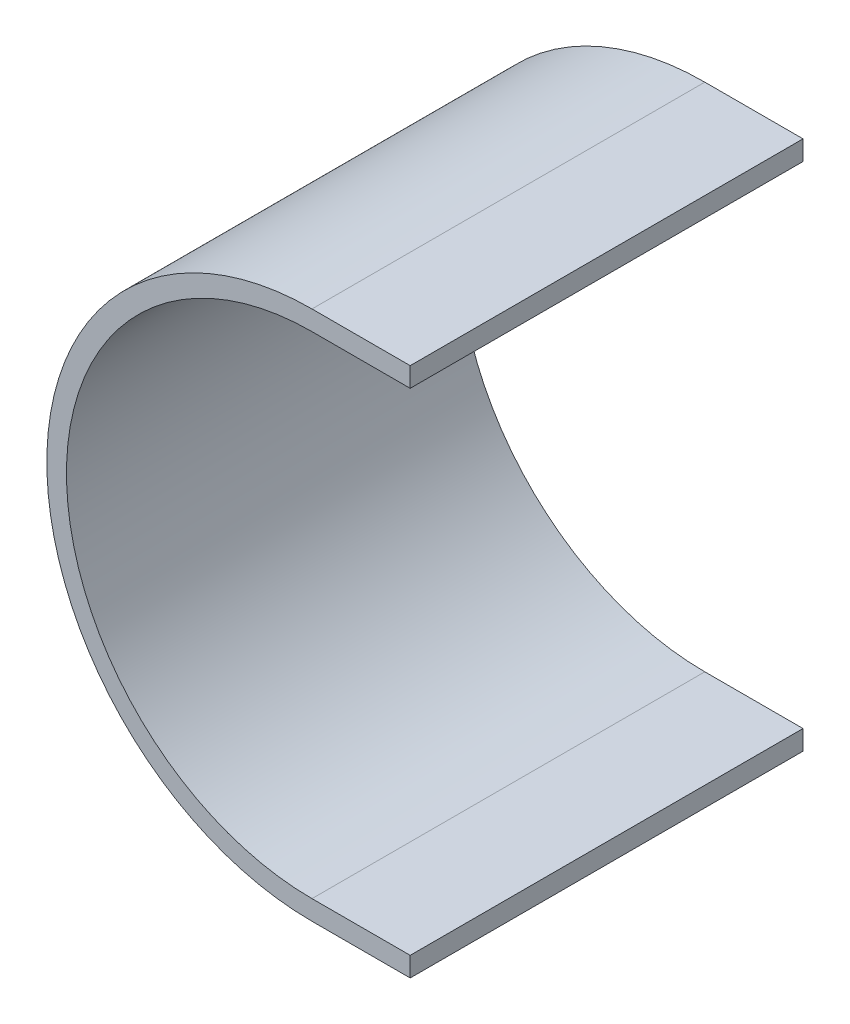
SolidWorks part; units mm, degrees
ref_plane "Front Plane" through (0, 0, 0) normal (0, 0, 1) x (1, 0, 0)
ref_plane "Top Plane" through (0, 0, 0) normal (0, 1, 0) x (1, 0, 0)
ref_plane "Right Plane" through (0, 0, 0) normal (1, 0, 0) x (0, 0, -1)
sketch "Sketch1" plane through (0, 0, 0) normal (0, 0, 1) x (1, 0, 0)
  line L3 (0, 81) -> (30, 81)
  line L5 (0, 75) -> (30, 75)
  line L6 (30, 81) -> (30, 75)
  line L7 (0, -81) -> (30, -81)
  line L9 (0, -75) -> (30, -75)
  line L10 (30, -81) -> (30, -75)
  arc A0 (0, 75) -> (0, -75) centre (0, 0) ccw
  arc A1 (0, 81) -> (0, -81) centre (0, 0) ccw
  dimension "D1" = 150
  dimension "D2" = 6
  dimension "D3" = 30
  dimension "D4" = 30
extrude "Boss-Extrude1" add sketch "Sketch1" along normal blind 120
